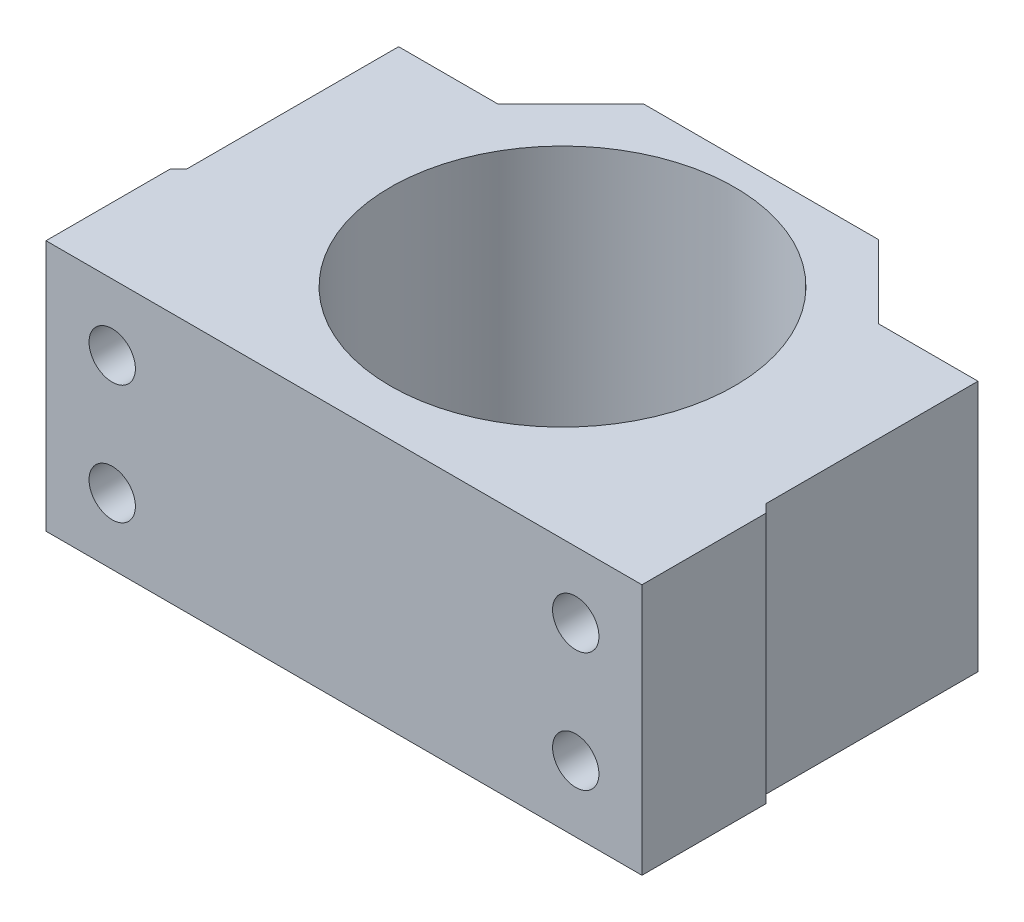
SolidWorks part; units mm, degrees
ref_plane "Front Plane" through (0, 0, 0) normal (0, 0, 1) x (1, 0, 0)
ref_plane "Top Plane" through (0, 0, 0) normal (0, 1, 0) x (1, 0, 0)
ref_plane "Right Plane" through (0, 0, 0) normal (1, 0, 0) x (0, 0, -1)
sketch "Sketch1" plane through (0, 0, 0) normal (0, 1, 0) x (1, 0, 0)
  line L0 (90, 0) -> (88.75, 0)
  line L1 (0, 0) -> (90, 0)
  line L2 (1.25, 52) -> (1.25, 20)
  line L3 (88.75, 52) -> (88.75, 20)
  line L6 (0, 0) -> (1.25, 0)
  line L10 (1.25, 52) -> (16.25, 52)
  line L11 (16.25, 52) -> (27.26, 63.01)
  line L12 (88.75, 52) -> (73.75, 52)
  line L13 (73.75, 52) -> (62.74, 63.01)
  line L14 (27.26, 63.01) -> (62.74, 63.01)
  line L16 (88.75, 20) -> (90, 18.75)
  line L18 (1.25, 20) -> (0, 18.75)
  line L19 (0, 18.75) -> (0, 0)
  line L20 (90, 18.75) -> (90, 0)
  line L21 (0, 0) -> (45, 0)
  circle A0 centre (45, 33) radius 26
extrude "Boss-Extrude1" add sketch "Sketch1" along normal blind 38 contours L20 L16 L3 L12 L13 L14 L11 L10 L2 L18 L19 L1 L0 A0
sketch "Sketch2" plane through (0, 0, 0) normal (0, 0, 1) x (1, 0, 0)
  line L0 (0, 0) -> (10, 0)
  line L1 (0, 0) -> (90, 0) construction
  circle A0 centre (10, 28) radius 3.5
  circle A1 centre (80, 28) radius 3.5
  circle A2 centre (80, 10) radius 3.5
  circle A3 centre (10, 10) radius 3.5
extrude "Cut-Extrude1" cut sketch "Sketch2" against normal through all contours A0 | A3 | A1 | A2
